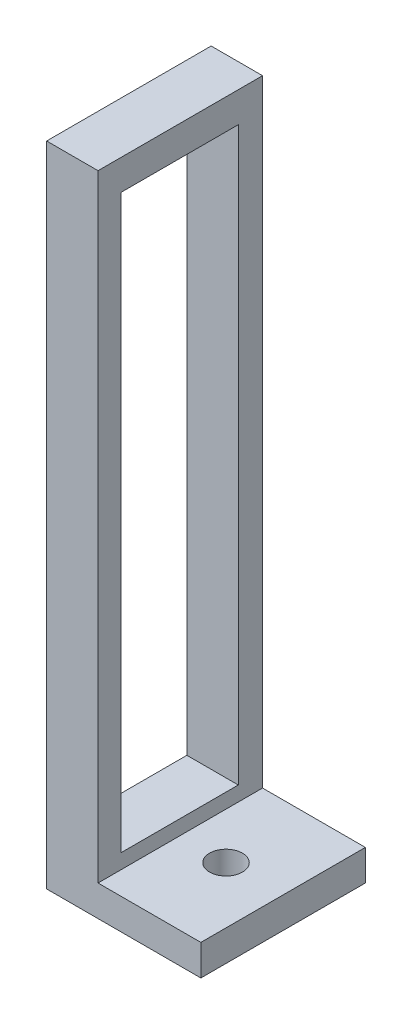
SolidWorks part; units mm, degrees
ref_plane "前视基准面" through (0, 0, 0) normal (0, 0, 1) x (1, 0, 0)
ref_plane "上视基准面" through (0, 0, 0) normal (0, 1, 0) x (1, 0, 0)
ref_plane "右视基准面" through (0, 0, 0) normal (1, 0, 0) x (0, 0, -1)
sketch "草图1" plane through (0, 0, 0) normal (0, 0, 1) x (1, 0, 0)
  line L1 (0, 0) -> (5, 0)
  line L2 (0, 0) -> (0, 63)
  line L3 (0, 63) -> (5, 63)
  line L4 (5, 3) -> (5, 63)
  line L5 (0, 0) -> (15, 0)
  line L6 (0, 0) -> (0, 3)
  line L7 (5, 3) -> (15, 3)
  line L8 (15, 0) -> (15, 3)
  dimension "D1" = 63
  dimension "D2" = 5
  dimension "D3" = 15
  dimension "D4" = 3
extrude "凸台-拉伸1" add sketch "草图1" along normal blind 16 contours L5 L8 L7 L4 L3 L2 L1
sketch "草图2" plane through (5, 0, 0) normal (1, 0, 0) x (0, 0, -1)
  line L1 (-13.7815, 60.0527) -> (-2.3604, 60.0527)
  line L2 (-13.7815, 60.0527) -> (-13.7815, 4.437)
  line L3 (-13.7815, 4.437) -> (-2.3604, 4.437)
  line L4 (-2.3604, 60.0527) -> (-2.3604, 4.437)
extrude "切除-拉伸1" cut sketch "草图2" against normal blind 16
sketch "草图3" plane through (0, 3, 0) normal (0, 1, 0) x (1, 0, 0)
  circle A0 centre (9.5036, -8.0589) radius 1.6
  dimension "D1" = 3.2
extrude "切除-拉伸2" cut sketch "草图3" against normal blind 16
